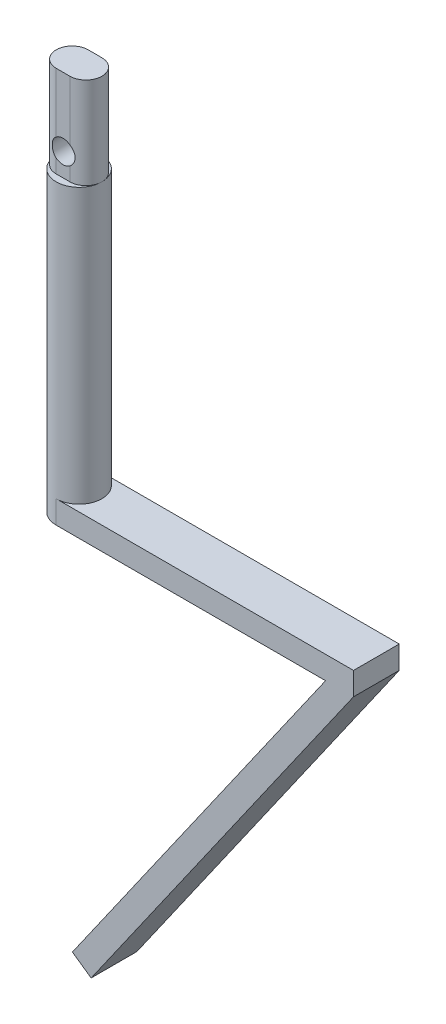
SolidWorks part; units mm, degrees
ref_plane "Front Plane" through (0, 0, 0) normal (0, 0, 1) x (1, 0, 0)
ref_plane "Top Plane" through (0, 0, 0) normal (0, 1, 0) x (1, 0, 0)
ref_plane "Right Plane" through (0, 0, 0) normal (1, 0, 0) x (0, 0, -1)
sketch "Sketch1" plane through (0, 0, 0) normal (0, 1, 0) x (1, 0, 0)
  circle A0 centre (0, 0) radius 5
  dimension "D1" = 10
extrude "Boss-Extrude1" add sketch "Sketch1" along normal blind 60
sketch "Sketch2" plane through (0, 60, 0) normal (0, 1, 0) x (1, 0, 0)
  line L0 (1.5, 0) -> (-1.5, 0) construction
  line L1 (1.5, -3.5) -> (-1.5, -3.5)
  line L2 (1.5, 3.5) -> (-1.5, 3.5)
  arc A0 (1.5, -3.5) -> (1.5, 3.5) centre (1.5, 0) ccw
  arc A1 (-1.5, 3.5) -> (-1.5, -3.5) centre (-1.5, 0) ccw
  point P2 (0, 0)
  point P8 (-5, 0)
  point P9 (5, 0)
  dimension "D1" = 10
  dimension "D2" = 7
extrude "Boss-Extrude2" add sketch "Sketch2" along normal blind 20
sketch "Sketch3" plane through (0, 0, 3.5) normal (0, 0, 1) x (1, 0, 0)
  line L0 (5, 60) -> (5, 80) construction
  line L1 (5, 60) -> (-5, 60) construction
  circle A0 centre (0, 65) radius 2.5
  dimension "D2" = 5
  dimension "D1" = 5
  dimension "D3" = 5
extrude "Cut-Extrude1" cut sketch "Sketch3" against normal blind 15
sketch "Sketch4" plane through (0, 0, 0) normal (0, -1, 0) x (1, 0, 0)
  line L0 (0, 0) -> (65, 0) construction
  line L1 (0, 5) -> (65, 5)
  line L2 (0, -5) -> (65, -5)
  line L3 (65, 5) -> (65, -5)
  arc A0 (0, 5) -> (0, -5) centre (0, 0) ccw
  point P3 (45, 0)
  dimension "D1" = 10
  dimension "D2" = 65
extrude "Boss-Extrude3" add sketch "Sketch4" along normal blind 5
sketch "Sketch6" plane through (0, 0, 5) normal (0, 0, 1) x (1, 0, 0)
  line L0 (65, -5) -> (7.6424, -86.9152)
  line L1 (65, -5) -> (0, -5) construction
  line L2 (65, -5) -> (65, 0) construction
  line L3 (7.6424, -86.9152) -> (3.5466, -84.0473)
  line L4 (3.5466, -84.0473) -> (58.8961, -5)
  line L5 (58.8961, -5) -> (65, -5)
  dimension "D1" = 5
  dimension "D2" = 100
  dimension "D3" = 55
extrude "Boss-Extrude5" add sketch "Sketch6" against normal up to surface (10 mm away) up to face at (32.5, -2.5, -5)
